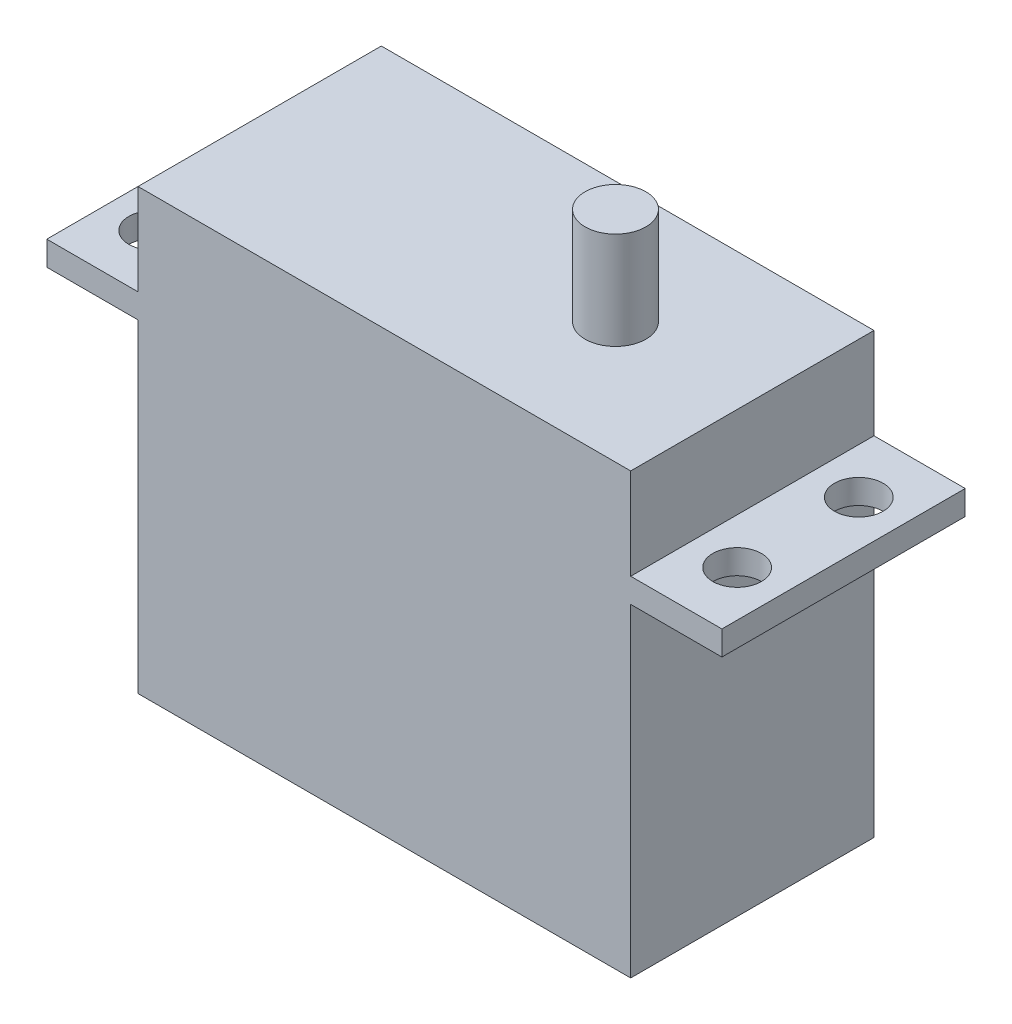
SolidWorks part; units mm, degrees
material "Plain Carbon Steel"
ref_plane "Front Plane" through (0, 0, 0) normal (0, 0, 1) x (1, 0, 0)
ref_plane "Top Plane" through (0, 0, 0) normal (0, 1, 0) x (1, 0, 0)
ref_plane "Right Plane" through (0, 0, 0) normal (1, 0, 0) x (0, 0, -1)
sketch "Sketch1" plane through (0, 0, 0) normal (0, 1, 0) x (1, 0, 0)
  line L1 (-16.7433, 10.7539) -> (23.7567, 10.7539)
  line L2 (-16.7433, 10.7539) -> (-16.7433, -9.2461)
  line L3 (-16.7433, -9.2461) -> (23.7567, -9.2461)
  line L4 (23.7567, 10.7539) -> (23.7567, -9.2461)
  dimension "D1" = 40.5
  dimension "D2" = 20
extrude "Boss-Extrude1" add sketch "Sketch1" along normal blind 36.1
sketch "Sketch2" plane through (0, 36.1, 0) normal (0, 1, 0) x (1, 0, 0)
  line L0 (23.7567, 10.7539) -> (-16.7433, 10.7539) construction
  line L1 (23.7567, -9.2461) -> (23.7567, 10.7539) construction
  circle A0 centre (12.5067, 0.7539) radius 2.5
  dimension "D1" = 10
  dimension "D2" = 11.25
extrude "Boss-Extrude2" add sketch "Sketch2" along normal blind 8
sketch "Sketch3" plane through (-16.7433, 0, 0) normal (-1, 0, 0) x (0, 0, 1)
  line L0 (-10.7539, 36.1) -> (-10.7539, 0) construction
  line L1 (-10.7539, 28.6) -> (9.2461, 28.6)
  line L2 (-10.7539, 28.6) -> (-10.7539, 26.6)
  line L3 (-10.7539, 26.6) -> (9.2461, 26.6)
  line L4 (9.2461, 28.6) -> (9.2461, 26.6)
  line L5 (9.2461, 36.1) -> (9.2461, 0) construction
  line L6 (-10.7539, 0) -> (9.2461, 0) construction
  dimension "D1" = 26.6
  dimension "D2" = 2
extrude "Boss-Extrude3" add sketch "Sketch3" along normal blind 7.5 and the other way blind 48
sketch "Sketch4" plane through (0, 28.6, 0) normal (0, 1, 0) x (1, 0, 0)
  line L0 (23.7567, 10.7539) -> (-16.7433, 10.7539) construction
  line L1 (-16.7433, -9.2461) -> (23.7567, -9.2461) construction
  line L2 (-16.7433, 10.7539) -> (-24.2433, 10.7539) construction
  line L3 (31.2567, 10.7539) -> (23.7567, 10.7539) construction
  circle A0 centre (-20.4933, 5.7539) radius 2
  circle A1 centre (27.5067, 5.7539) radius 2
  circle A2 centre (-20.4933, -4.2461) radius 2
  circle A3 centre (27.5067, -4.2461) radius 2
  point P8 (3.5067, 10.7539)
  point P11 (3.5067, -9.2461)
  point P14 (3.5067, -9.2461)
  point P15 (3.5067, 10.7539)
  point P16 (-20.4933, 10.7539)
  dimension "D1" = 24
  dimension "D2" = 24
  dimension "D3" = 24
  dimension "D4" = 24
  dimension "D5" = 10
  dimension "D6" = 10
  dimension "D7" = 5
  dimension "D8" = 5
extrude "Cut-Extrude1" cut sketch "Sketch4" against normal blind 7.5
